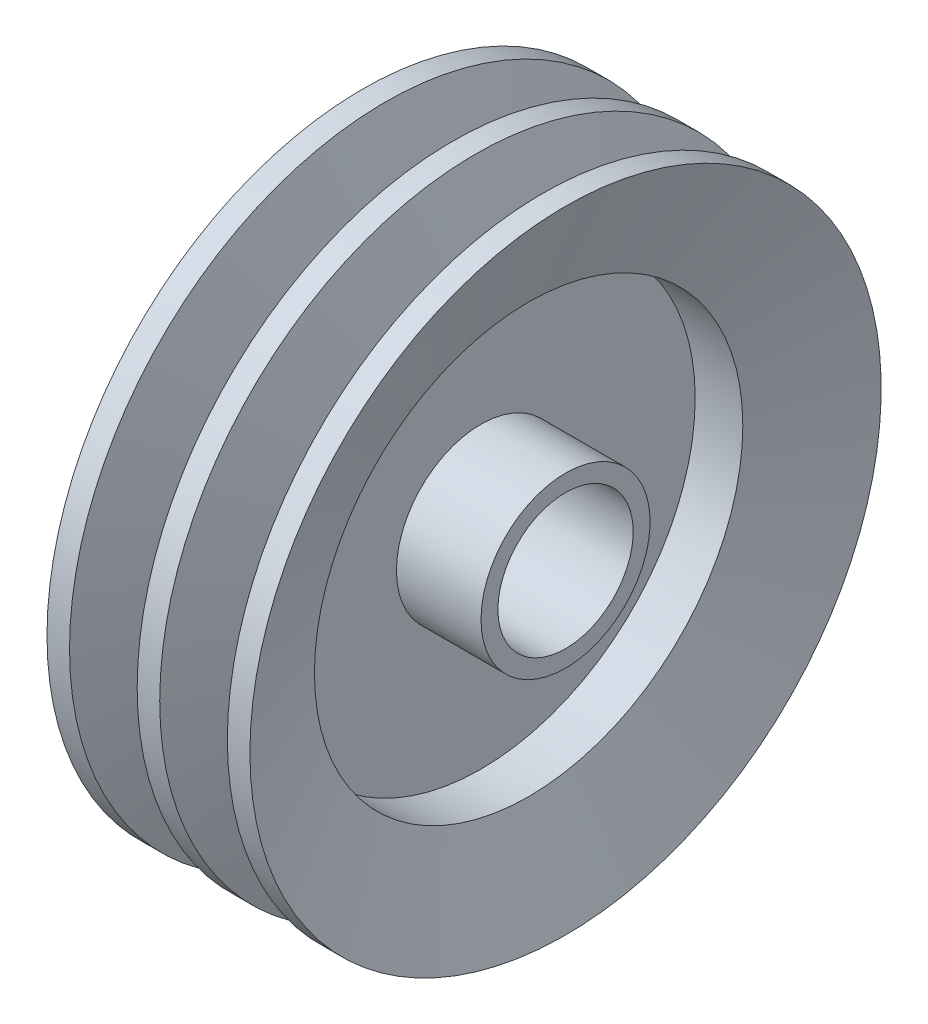
SolidWorks part; units mm, degrees
ref_plane "Alzado" through (0, 0, 0) normal (0, 0, 1) x (1, 0, 0)
ref_plane "Planta" through (0, 0, 0) normal (0, 1, 0) x (1, 0, 0)
ref_plane "Vista lateral" through (0, 0, 0) normal (1, 0, 0) x (0, 0, -1)
sketch "Croquis1" plane through (0, 0, 0) normal (0, 1, 0) x (1, 0, 0)
  line L0 (0, 0) -> (0, 110) construction
  line L1 (-5, 110) -> (5, 110)
  line L2 (5, 110) -> (15.9191, 80)
  line L3 (15.9191, 80) -> (24.0809, 80)
  line L4 (24.0809, 80) -> (35, 110)
  line L5 (35, 110) -> (45, 110)
  line L6 (45, 110) -> (28.6213, 65)
  line L7 (28.6213, 65) -> (7.5, 65)
  line L8 (7.5, 65) -> (7.5, 7.5)
  line L9 (7.5, 7.5) -> (45, 7.5)
  line L10 (45, 7.5) -> (45, 0)
  line L11 (45, 0) -> (-45, 0)
  line L12 (-45, 7.5) -> (-45, 0)
  line L13 (-7.5, 7.5) -> (-45, 7.5)
  line L14 (-7.5, 65) -> (-7.5, 7.5)
  line L15 (-28.6213, 65) -> (-7.5, 65)
  line L16 (-45, 110) -> (-28.6213, 65)
  line L17 (-35, 110) -> (-45, 110)
  line L18 (-24.0809, 80) -> (-35, 110)
  line L19 (-15.9191, 80) -> (-24.0809, 80)
  line L20 (-5, 110) -> (-15.9191, 80)
  line L21 (-45, -30) -> (45, -30) construction
  point P23 (20, 80)
  point P30 (45, 3.75)
  dimension "D1" = 90
  dimension "D2" = 30
  dimension "D3" = 15
  dimension "D4" = 10
  dimension "D5" = 40
  dimension "D6" = 30
  dimension "D7" = 280
  dimension "D8" = 190
  dimension "D9" = 75
  dimension "D10" = 60
revolve "Revolución1" add sketch "Croquis1" angle 360 about L21
